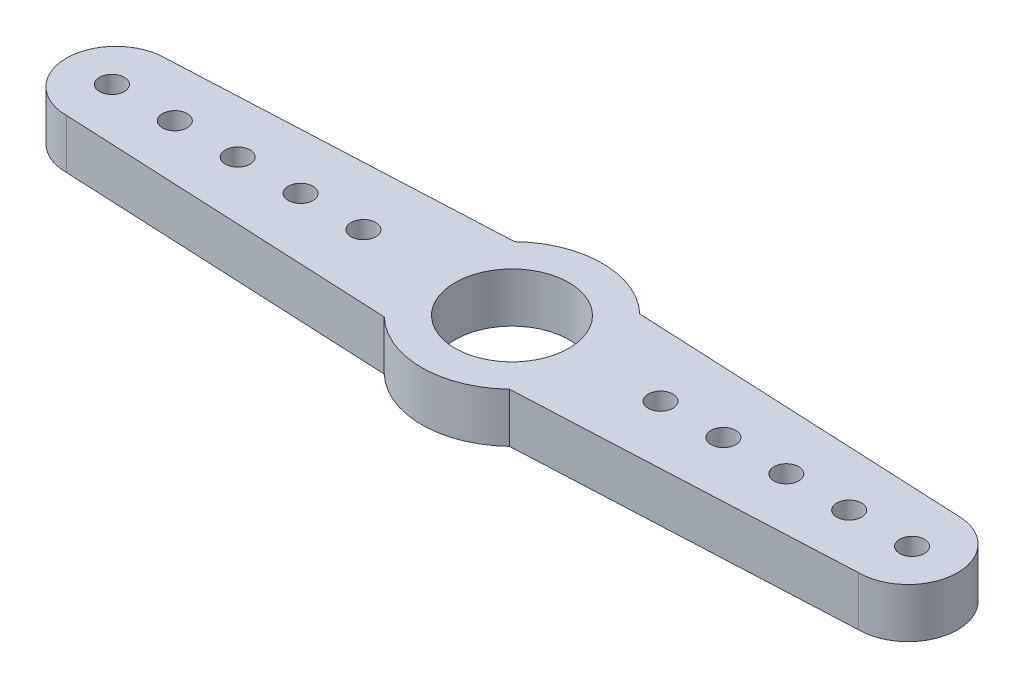
SolidWorks part; units mm, degrees
ref_plane "Front Plane" through (0, 0, 0) normal (0, 0, 1) x (1, 0, 0)
ref_plane "Top Plane" through (0, 0, 0) normal (0, 1, 0) x (1, 0, 0)
ref_plane "Right Plane" through (0, 0, 0) normal (1, 0, 0) x (0, 0, -1)
sketch "Sketch1" plane through (0, 0, 0) normal (0, 1, 0) x (1, 0, 0)
  line L0 (-16, -2) -> (-2.5285, -2.6325)
  line L1 (2.5285, -2.6325) -> (16, -2)
  line L2 (16, 2) -> (2.528, 2.6326)
  line L3 (-2.528, 2.6326) -> (-16, 2)
  line L4 (-6, 0) -> (-8.54, 0) construction
  line L5 (-8.54, 0) -> (-11.08, 0) construction
  line L6 (-11.08, 0) -> (-13.62, 0) construction
  line L7 (-13.62, 0) -> (-16.16, 0) construction
  line L8 (0, 3.45) -> (0, -3.45) construction
  line L9 (11.08, 0) -> (13.62, 0) construction
  line L10 (8.54, 0) -> (11.08, 0) construction
  line L11 (6, 0) -> (8.54, 0) construction
  line L12 (13.62, 0) -> (16.16, 0) construction
  circle A0 centre (0, -0.0002) radius 3.65 construction
  circle A1 centre (0, 0) radius 2.3
  circle A2 centre (-6, 0) radius 0.5
  circle A3 centre (-8.54, 0) radius 0.5
  circle A4 centre (-11.08, 0) radius 0.5
  circle A5 centre (-13.62, 0) radius 0.5
  circle A6 centre (-16.16, 0) radius 0.5
  circle A7 centre (16.16, 0) radius 0.5
  circle A8 centre (13.62, 0) radius 0.5
  circle A9 centre (11.08, 0) radius 0.5
  circle A10 centre (8.54, 0) radius 0.5
  circle A11 centre (6, 0) radius 0.5
  circle A12 centre (-16, 0) radius 2 construction
  arc A13 (16, -2) -> (14.0222, -0.2971) centre (16, 0) ccw construction
  arc A14 (2.528, 2.6326) -> (-2.528, 2.6326) centre (0, -0.0002) ccw
  arc A15 (-2.5285, -2.6325) -> (2.5285, -2.6325) centre (0, -0.0002) ccw
  arc A16 (-16, -2) -> (-16, 2) centre (-16, 0) cw
  arc A17 (16, 2) -> (16, -2) centre (16, 0) cw
  point P14 (0, -0.0002)
  point P38 (0, 0)
  dimension "D1" = 7.3
  dimension "D2" = 1
  dimension "D4" = 1
  dimension "D6" = 1
  dimension "D8" = 1
  dimension "D10" = 1
  dimension "D11" = 4
  dimension "D12" = 4
  dimension "D3" = 2.54
  dimension "D5" = 2.54
  dimension "D7" = 2.54
  dimension "D9" = 2.54
  dimension "D13" = 32
  dimension "D14" = 16
extrude "Boss-Extrude1" add sketch "Sketch1" along normal blind 2
